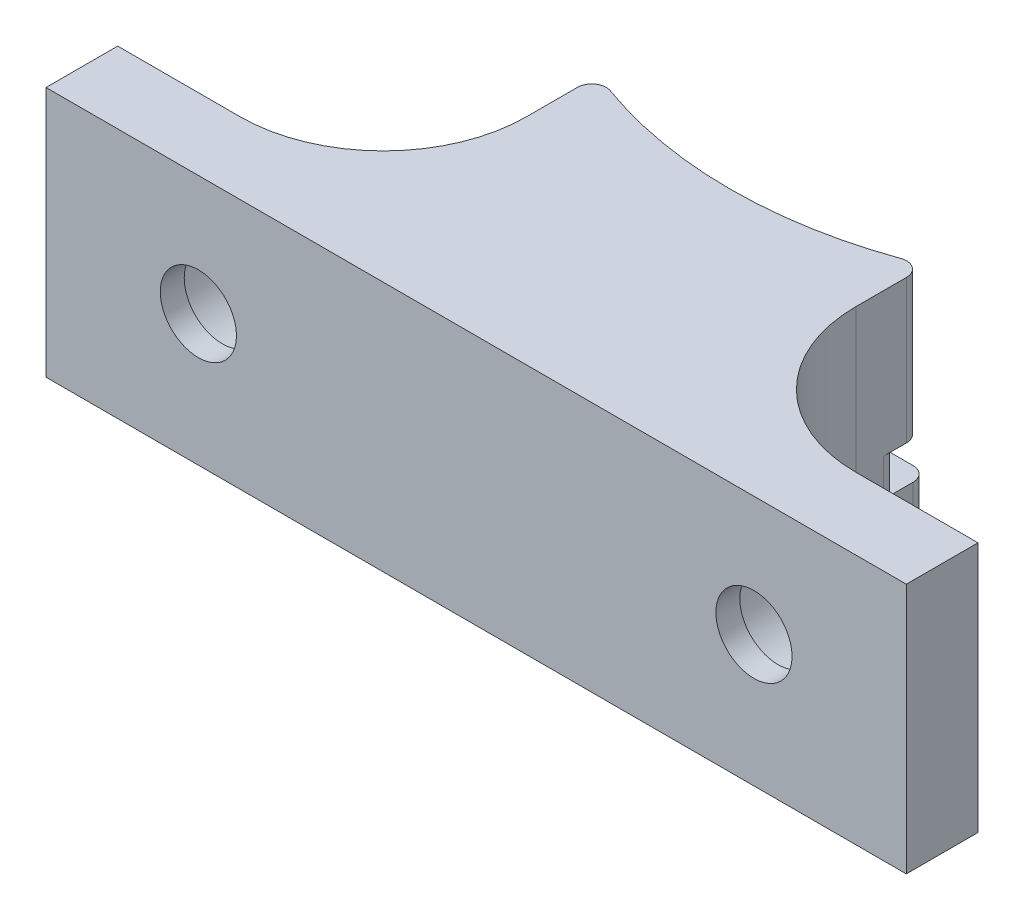
SolidWorks part; units mm, degrees
other "Markup1"
sketch "Sketch4" plane through (-125.7365, 25.4, -65.9837) normal (-0.2855, 0.1861, -0.9401) x (-0.9569, -0.1093, 0.269)
ref_plane "Front Plane" through (0, 0, 0) normal (0, 0, 1) x (1, 0, 0)
ref_plane "Top Plane" through (0, 0, 0) normal (0, 1, 0) x (1, 0, 0)
ref_plane "Right Plane" through (0, 0, 0) normal (1, 0, 0) x (0, 0, -1)
sketch "Sketch1" plane through (0, 0, 0) normal (0, 1, 0) x (1, 0, 0)
  line L0 (29.1508, 25.4) -> (0, 95.7762) construction
  line L1 (76.2, 25.4) -> (-76.2, 25.4)
  line L2 (76.2, 25.4) -> (76.2, -25.4)
  line L3 (76.2, -25.4) -> (-76.2, -25.4)
  line L4 (-76.2, 25.4) -> (-76.2, -25.4)
  line L5 (76.2, 25.4) -> (-76.2, -25.4) construction
  line L6 (76.2, -25.4) -> (-76.2, 25.4) construction
  line L7 (0, 95.7762) -> (-29.1508, 25.4) construction
  arc A0 (-29.1508, 25.4) -> (29.1508, 25.4) centre (0, 95.7762) ccw
  point P0 (0, 0)
  dimension "D1" = 76.1746
  dimension "D2" = 45
  dimension "D3" = 152.4
  dimension "D4" = 50.8
extrude "Boss-Extrude1" add sketch "Sketch1" along normal blind 25.4 contours A0 L1 L4 L3 L2
sketch "Sketch2" plane through (0, 0, 0) normal (0, -1, 0) x (1, 0, 0)
  line L1 (-76.2, 25.4) -> (76.2, 25.4)
  line L6 (-76.2, 25.4) -> (-76.2, -21.59)
  line L7 (-76.2, -25.4) -> (-76.2, 25.4) construction
  line L8 (-76.2, -21.59) -> (-29.9669, -21.59)
  line L9 (76.2, 25.4) -> (76.2, -21.59)
  line L10 (76.2, -21.59) -> (29.9669, -21.59)
  line L11 (-29.1508, -25.4) -> (-76.2, -25.4) construction
  arc A1 (-29.9669, -21.59) -> (29.9669, -21.59) centre (0, -95.7762) cw
  arc A3 (29.1508, -25.4) -> (-29.1508, -25.4) centre (0, -95.7762) ccw construction
  dimension "D1" = 80.01
  dimension "D2" = 3.81
extrude "Boss-Extrude2" add sketch "Sketch2" along normal blind 6.604
sketch "Sketch3" plane through (0, -6.604, 0) normal (0, -1, 0) x (1, 0, 0)
  line L0 (76.2, -21.59) -> (76.2, 25.4) construction
  line L1 (-76.2, 25.4) -> (76.2, 25.4)
  line L2 (-76.2, 25.4) -> (-76.2, -25.4)
  line L3 (-76.2, -25.4) -> (76.2, -25.4)
  line L4 (76.2, 25.4) -> (76.2, -25.4)
  line L5 (76.2, -25.4) -> (29.1508, -25.4) construction
extrude "Boss-Extrude3" add sketch "Sketch3" along normal blind 12.446
sketch "Sketch5" plane through (0, 25.4, 0) normal (0, 1, 0) x (1, 0, 0)
  line L0 (-29.1508, 25.4) -> (-29.1508, -12.7)
  line L1 (-29.1508, -12.7) -> (-76.2, -12.7)
  line L2 (-76.2, 25.4) -> (-76.2, -25.4) construction
  line L3 (-76.2, -12.7) -> (-76.2, 25.4)
  line L4 (-76.2, 25.4) -> (76.2, 25.4)
  line L5 (76.2, 25.4) -> (76.2, -12.7)
  line L6 (76.2, -12.7) -> (29.1508, -12.7)
  line L7 (29.1508, -12.7) -> (29.1508, 25.4)
  line L8 (76.2, 25.4) -> (76.2, -25.4) construction
  line L9 (-29.1508, 25.4) -> (-76.2, 25.4) construction
  line L10 (76.2, -25.4) -> (-76.2, -25.4) construction
  arc A0 (-29.1508, 25.4) -> (29.1508, 25.4) centre (0, 95.7762) ccw
  arc A3 (-29.1508, 25.4) -> (29.1508, 25.4) centre (0, 95.7762) ccw construction
  line M8 (-29.1508, 25.4) -> (-76.2, 25.4)
  line M9 (-76.2, 25.4) -> (-76.2, -25.4)
  line M11 (76.2, -25.4) -> (76.2, 25.4)
  line M12 (76.2, 25.4) -> (29.1508, 25.4)
  dimension "D1" = 12.7
extrude "Cut-Extrude1" cut sketch "Sketch5" against normal through all contours L1 L0 M8 M9 | L7 L6 M11 M12
fillet "Fillet1" radius 2.54 6 edges at (29.1508, -12.827, -25.4) (-29.1508, -12.827, -25.4) (-29.1508, -3.302, -21.2655) (29.1508, -3.302, -21.2655) (29.1508, 12.7, -25.4) (-29.1508, 12.7, -25.4)
fillet "Fillet2" radius 25.4 2 edges at (29.1508, 3.175, 12.7) (-29.1508, 3.175, 12.7)
sketch "Sketch6" plane through (0, 0, 0) normal (0, 0, 1) x (1, 0, 0)
  line L0 (49.2125, 4.191) -> (-49.2125, 4.191) construction
  line L1 (29.1508, -19.05) -> (54.5508, -19.05) construction
  circle A0 centre (49.2125, 4.191) radius 9.9187
  circle A1 centre (-49.2125, 4.191) radius 9.9187
  point P4 (0, 4.191)
  dimension "D1" = 98.425
  dimension "D3" = 19.8374
  dimension "D2" = 23.241
extrude "Cut-Extrude2" cut sketch "Sketch6" along normal offset from surface 4.2418 and the other way through all from surface at 12.7 up to face at (0, 3.175, 25.4) starting at face at (65.3754, 3.175, 12.7)
sketch "Sketch7" plane through (0, 0, 21.1582) normal (0, 0, -1) x (-1, 0, 0)
  circle A0 centre (-49.2125, 4.191) radius 6.7437
  circle A1 centre (49.2125, 4.191) radius 6.7437
  arc A2 (-54.5508, -4.1686) -> (-54.5508, 12.5506) centre (-49.2125, 4.191) ccw construction
  circle A3 centre (49.2125, 4.191) radius 9.9187 construction
  dimension "D1" = 13.4874
extrude "Cut-Extrude3" cut sketch "Sketch7" against normal through all
